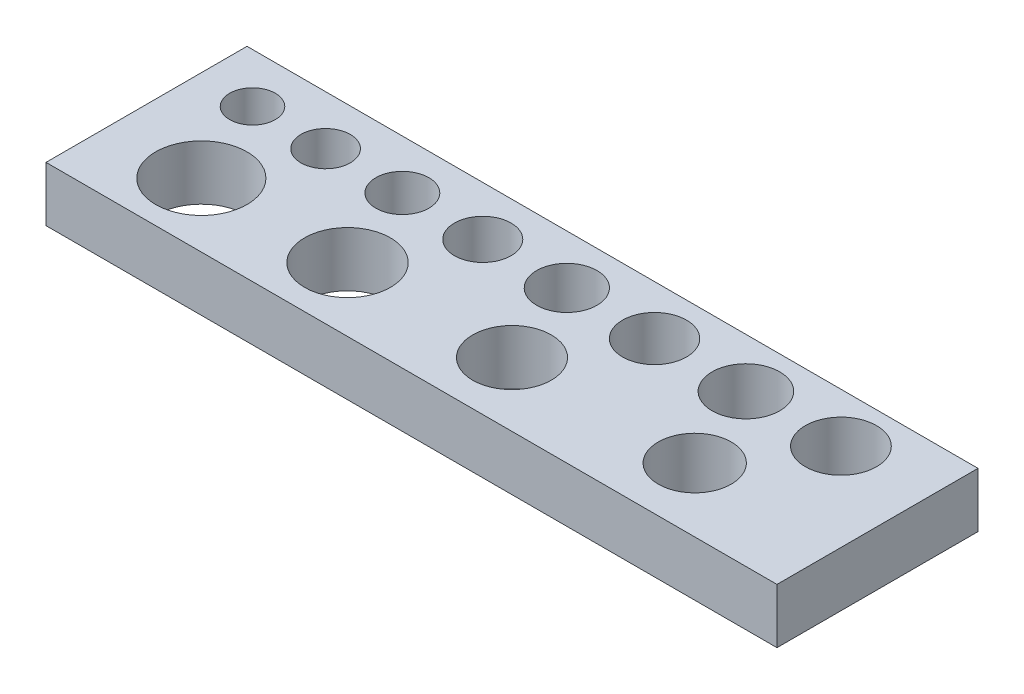
SolidWorks part; units mm, degrees
ref_plane "Front Plane" through (0, 0, 0) normal (0, 0, 1) x (1, 0, 0)
ref_plane "Top Plane" through (0, 0, 0) normal (0, 1, 0) x (1, 0, 0)
ref_plane "Right Plane" through (0, 0, 0) normal (1, 0, 0) x (0, 0, -1)
sketch "Sketch1" plane through (0, 0, 0) normal (0, 1, 0) x (1, 0, 0)
  line L1 (20, -5.5) -> (-20, -5.5)
  line L2 (20, -5.5) -> (20, 5.5)
  line L3 (20, 5.5) -> (-20, 5.5)
  line L4 (-20, -5.5) -> (-20, 5.5)
  line L5 (20, -5.5) -> (-20, 5.5) construction
  line L6 (20, 5.5) -> (-20, -5.5) construction
  point P0 (0, 0)
  dimension "D1" = 40
  dimension "D2" = 11
extrude "Boss-Extrude1" add sketch "Sketch1" along normal blind 3
sketch "Sketch2" plane through (0, 3, 0) normal (0, 1, 0) x (1, 0, 0)
  line L0 (-20, 2.8) -> (20, 2.8) construction
  line L1 (-20, 5.5) -> (-20, -5.5) construction
  line L3 (20, 5.5) -> (-20, 5.5) construction
  line L4 (20, -5.5) -> (20, 5.5) construction
  line L5 (-20, -2) -> (20, -2) construction
  line L6 (-20, -5.5) -> (20, -5.5) construction
  circle A0 centre (-17, 2.8) radius 1.25
  circle A1 centre (-13, 2.8) radius 1.35
  circle A2 centre (-8.8, 2.8) radius 1.45
  circle A3 centre (-4.4, 2.8) radius 1.55
  circle A4 centre (0.2, 2.8) radius 1.65
  circle A5 centre (5, 2.8) radius 1.75
  circle A6 centre (10, 2.8) radius 1.85
  circle A7 centre (15.2, 2.8) radius 1.95
  circle A9 centre (2, -2) radius 2.15
  circle A10 centre (12, -2) radius 2
  circle A11 centre (-15, -2) radius 2.5
  circle A12 centre (-7, -2) radius 2.35
  dimension "D1" = 2.5
  dimension "D4" = 2.7
  dimension "D6" = 2.9
  dimension "D8" = 3.1
  dimension "D9" = 4.6
  dimension "D10" = 3.3
  dimension "D11" = 3.5
  dimension "D12" = 4.8
  dimension "D13" = 5
  dimension "D14" = 5.2
  dimension "D15" = 3.7
  dimension "D16" = 3.9
  dimension "D19" = 4
  dimension "D21" = 4.3
  dimension "D22" = 5
  dimension "D23" = 4.7
  dimension "D24" = 5
  dimension "D25" = 8
  dimension "D26" = 9
  dimension "D20" = 10
  dimension "D2" = 3
  dimension "D3" = 4
  dimension "D5" = 4.2
  dimension "D7" = 4.4
  dimension "D17" = 2.7
  dimension "D18" = 3.5
extrude "Cut-Extrude1" cut sketch "Sketch2" against normal through all
